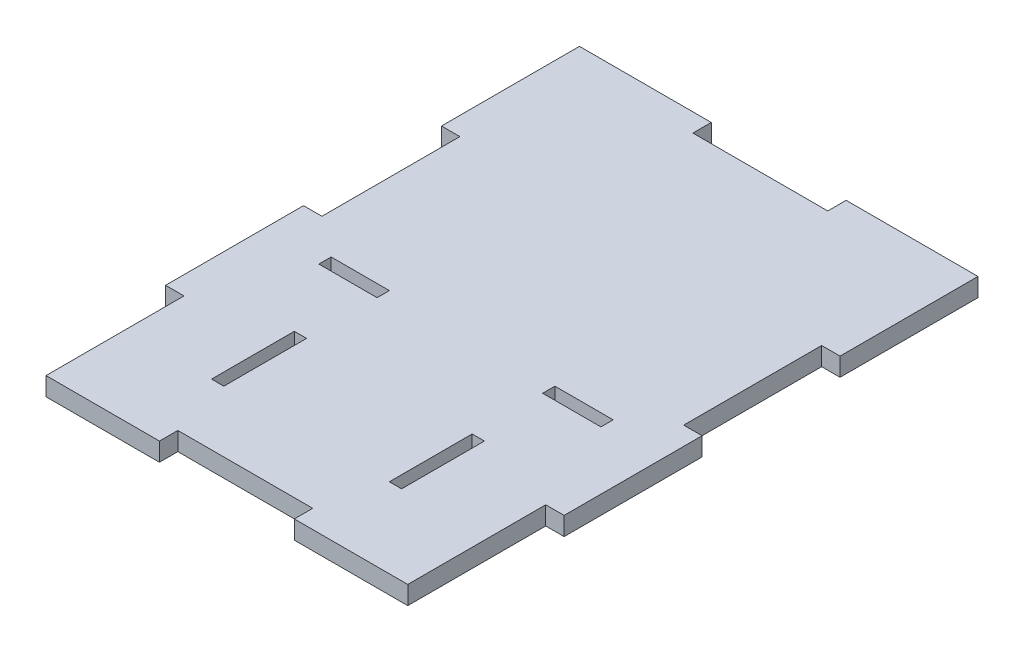
SolidWorks part; units mm, degrees
ref_plane "Front" through (0, 0, 0) normal (0, 0, 1) x (1, 0, 0)
ref_plane "Top" through (0, 0, 0) normal (0, 1, 0) x (1, 0, 0)
ref_plane "Right" through (0, 0, 0) normal (1, 0, 0) x (0, 0, -1)
sketch "Sketch1" plane through (0, 0, 0) normal (0, 1, 0) x (1, 0, 0)
  line L1 (0, 0) -> (130, 0)
  line L2 (0, 0) -> (0, 180)
  line L3 (0, 180) -> (130, 180)
  line L4 (130, 0) -> (130, 180)
  dimension "D1" = 130
  dimension "D2" = 180
extrude "Boss-Extrude1" add sketch "Sketch1" along normal blind 6
sketch "Sketch2" plane through (0, 6, 0) normal (0, 1, 0) x (1, 0, 0)
  line L0 (130, 180) -> (0, 180) construction
  line L1 (0, 180) -> (43, 180)
  line L2 (0, 180) -> (0, 174)
  line L3 (0, 174) -> (43, 174)
  line L4 (43, 180) -> (43, 174)
  line L5 (43, 174) -> (87, 174)
  line L6 (43, 174) -> (43, 180)
  line L7 (43, 180) -> (87, 180)
  line L8 (87, 174) -> (87, 180)
  line L9 (0, 0) -> (130, 0) construction
  line L10 (0, 0) -> (43, 0)
  line L11 (0, 0) -> (0, 6)
  line L12 (0, 6) -> (43, 6)
  line L13 (43, 0) -> (43, 6)
  line L14 (43, 6) -> (87, 6)
  line L15 (43, 6) -> (43, 0)
  line L16 (43, 0) -> (87, 0)
  line L17 (87, 6) -> (87, 0)
  line L19 (0, 0) -> (6, 0)
  line L20 (0, 0) -> (0, 45)
  line L21 (0, 45) -> (6, 45)
  line L22 (6, 0) -> (6, 45)
  line L23 (0, 45) -> (6, 45)
  line L24 (0, 45) -> (0, 90)
  line L25 (0, 90) -> (6, 90)
  line L26 (6, 45) -> (6, 90)
  line L27 (0, 90) -> (6, 90)
  line L28 (0, 90) -> (0, 135)
  line L29 (0, 135) -> (6, 135)
  line L30 (6, 90) -> (6, 135)
  line L31 (0, 135) -> (6, 135)
  line L32 (0, 135) -> (0, 180)
  line L33 (0, 180) -> (6, 180)
  line L34 (6, 135) -> (6, 180)
  line L35 (130, 180) -> (124, 180)
  line L36 (130, 180) -> (130, 135)
  line L37 (130, 135) -> (124, 135)
  line L38 (124, 180) -> (124, 135)
  line L39 (130, 135) -> (124, 135)
  line L40 (130, 135) -> (130, 90)
  line L41 (130, 90) -> (124, 90)
  line L42 (124, 135) -> (124, 90)
  line L43 (130, 90) -> (124, 90)
  line L44 (130, 90) -> (130, 45)
  line L45 (130, 45) -> (124, 45)
  line L46 (124, 90) -> (124, 45)
  line L47 (130, 45) -> (124, 45)
  line L48 (130, 45) -> (130, 0)
  line L49 (130, 0) -> (124, 0)
  line L50 (124, 45) -> (124, 0)
  line L51 (38, 0) -> (34, 0)
  line L52 (38, 0) -> (38, 26)
  line L53 (38, 26) -> (34, 26)
  line L54 (34, 0) -> (34, 26)
  line L55 (34, 26) -> (38, 26)
  line L56 (34, 26) -> (34, 53)
  line L57 (34, 53) -> (38, 53)
  line L58 (38, 26) -> (38, 53)
  line L59 (34, 53) -> (38, 53)
  line L60 (34, 53) -> (34, 80)
  line L61 (34, 80) -> (38, 80)
  line L62 (38, 53) -> (38, 80)
  line L63 (38, 80) -> (19, 80)
  line L64 (38, 80) -> (38, 76)
  line L65 (38, 76) -> (19, 76)
  line L66 (19, 80) -> (19, 76)
  line L67 (19, 76) -> (0, 76)
  line L68 (19, 76) -> (19, 80)
  line L69 (19, 80) -> (0, 80)
  line L70 (0, 76) -> (0, 80)
  line L71 (96, 0) -> (92, 0)
  line L72 (96, 0) -> (96, 26)
  line L73 (96, 26) -> (92, 26)
  line L74 (92, 0) -> (92, 26)
  line L75 (92, 26) -> (96, 26)
  line L76 (92, 26) -> (92, 53)
  line L77 (92, 53) -> (96, 53)
  line L78 (96, 26) -> (96, 53)
  line L79 (92, 53) -> (96, 53)
  line L80 (92, 53) -> (92, 80)
  line L81 (92, 80) -> (96, 80)
  line L82 (96, 53) -> (96, 80)
  line L83 (92, 80) -> (111, 80)
  line L84 (92, 80) -> (92, 76)
  line L85 (92, 76) -> (111, 76)
  line L86 (111, 80) -> (111, 76)
  line L87 (111, 80) -> (130, 80)
  line L88 (111, 80) -> (111, 76)
  line L89 (111, 76) -> (130, 76)
  line L90 (130, 80) -> (130, 76)
  line M32 (0, 180) -> (0, 0)
  line M33 (0, 0) -> (130, 0)
  line M34 (130, 0) -> (130, 180)
  dimension "D1" = 6
  dimension "D2" = 43
  dimension "D3" = 44
  dimension "D4" = 19
  dimension "D5" = 19
  dimension "D6" = 4
  dimension "D7" = 27
  dimension "D8" = 6
  dimension "D9" = 27
  dimension "D10" = 26
  dimension "D11" = 26
extrude "Cut-Extrude1" cut sketch "Sketch2" against normal through all contours L25 L30 L29 M32 | L12 L22 L21 M32 | L22 L12 M33 M32 | L45 L50 M33 M34 | L17 L14 L13 M33 | L37 L42 L41 M34 | L86 L83 L82 L85 | L80 L85 L82 L81 | L64 L63 L66 L65 | L56 L55 L58 L57 | L76 L75 L78 L77 | L6 L5 L8 L7
